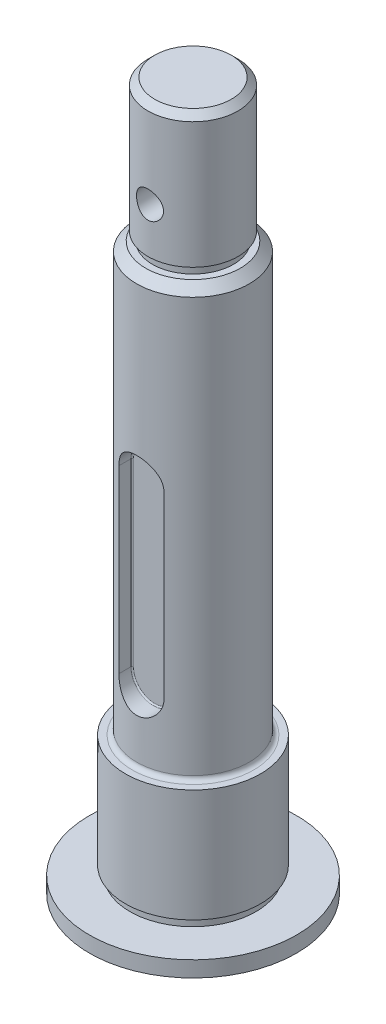
SolidWorks part; units mm, degrees
ref_plane "Спереди" through (0, 0, 0) normal (0, 0, 1) x (1, 0, 0)
ref_plane "Сверху" through (0, 0, 0) normal (0, 1, 0) x (1, 0, 0)
ref_plane "Справа" through (0, 0, 0) normal (1, 0, 0) x (0, 0, -1)
sketch "Эскиз1" plane through (0, 0, 0) normal (0, 0, 1) x (1, 0, 0)
  line L0 (0, 157) -> (0, 0)
  line L1 (0, 0) -> (23, 0)
  line L2 (23, 0) -> (23, 3.5)
  line L3 (23, 3.5) -> (14, 3.5)
  line L4 (14, 3.5) -> (14, 5.5)
  line L5 (14, 5.5) -> (15, 5.5)
  line L6 (15, 5.5) -> (15, 30.5)
  line L7 (15, 30.5) -> (13.5, 30.5)
  line L8 (12.5, 123.5) -> (12.5, 31.5)
  line L9 (12.5, 123.5) -> (0, 123.5) construction
  line L10 (10, 127.5) -> (9, 127.5)
  line L11 (10.5, 125.5) -> (9, 125.5)
  line L12 (9, 127.5) -> (9, 125.5)
  line L13 (10, 155.5) -> (0, 155.5) construction
  line L14 (10, 155.5) -> (8.5, 157)
  line L15 (10, 127.5) -> (10, 155.5)
  line L16 (8.5, 157) -> (0, 157)
  line L20 (12.5, 123.5) -> (10.5, 125.5)
  arc A0 (12.5, 31.5) -> (13.5, 30.5) centre (13.5, 31.5) ccw
  point P4 (0, 0)
  point P8 (18.5, 3.5)
  dimension "D17" = 1
  dimension "D1" = 3.5
  dimension "D2" = 23
  dimension "D3" = 2
  dimension "D4" = 15
  dimension "D5" = 14
  dimension "D6" = 25
  dimension "D7" = 2
  dimension "D8" = 45
  dimension "D9" = 95
  dimension "D10" = 10
  dimension "D11" = 45
  dimension "D12" = 1.5
  dimension "D13" = 2
  dimension "D14" = 9
  dimension "D15" = 12.5
  dimension "D16" = 157
revolve "Повернуть1" add sketch "Эскиз1" angle 360 about L0
ref_plane "Плоскость1" through (0, 0, 12.5) normal (0, 0, 1) x (1, 0, 0)
sketch "Эскиз2" plane through (0, 0, 12.5) normal (0, 0, 1) x (1, 0, 0)
  line L0 (0, 123.5) -> (0, 30.5) construction
  line L1 (-12.5, 123.5) -> (12.5, 123.5) construction
  line L2 (15, 30.5) -> (-15, 30.5) construction
  line L3 (5, 45.5) -> (5, 85.5)
  line L4 (-5, 85.5) -> (-5, 45.5)
  arc A0 (-5, 45.5) -> (5, 45.5) centre (0, 45.5) ccw
  arc A1 (5, 85.5) -> (-5, 85.5) centre (0, 85.5) ccw
  point P7 (0, 40.5)
  point P11 (0, 90.5)
  dimension "D1" = 10
  dimension "D2" = 10
  dimension "D3" = 50
extrude "Вырез-Вытянуть1" cut sketch "Эскиз2" against normal blind 4
fillet "Скругление1" radius 0.3 4 edges at (0, 40.5, 8.5) (5, 65.5, 8.5) (-5, 65.5, 8.5) (0, 90.5, 8.5)
ref_plane "Плоскость2" through (0, 0, 10) normal (0, 0, 1) x (1, 0, 0)
sketch "Эскиз3" plane through (0, 0, 10) normal (0, 0, 1) x (1, 0, 0)
  line L0 (10.5, 125.5) -> (-10.5, 125.5) construction
  line L1 (0, 127.5) -> (0, 155.5) construction
  line L2 (-9, 127.5) -> (9, 127.5) construction
  line L3 (-10, 155.5) -> (10, 155.5) construction
  circle A0 centre (0, 137.5) radius 3
  dimension "D1" = 12
  dimension "D2" = 6
extrude "Вырез-Вытянуть2" cut sketch "Эскиз3" against normal blind 25
